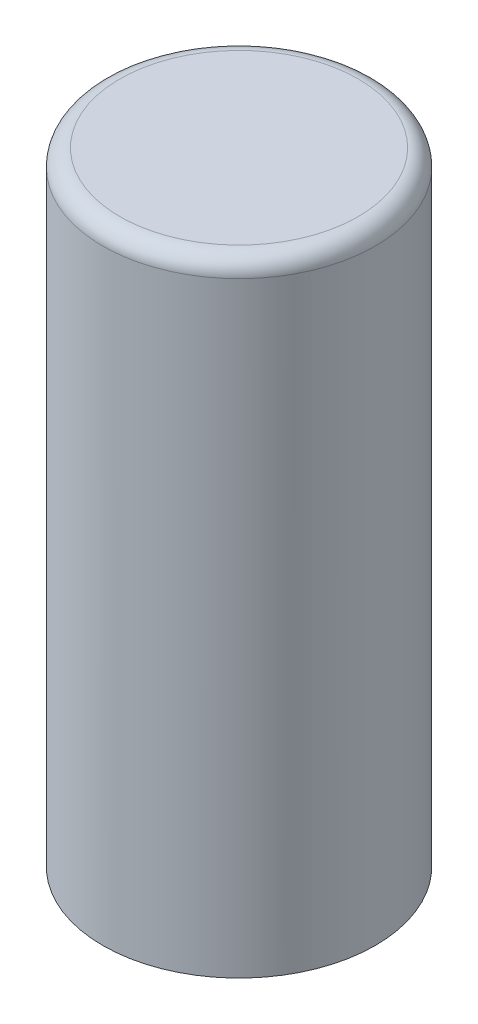
SolidWorks part; units mm, degrees
material "6061-T6 (SS)"
ref_plane "Front Plane" through (0, 0, 0) normal (0, 0, 1) x (1, 0, 0)
ref_plane "Top Plane" through (0, 0, 0) normal (0, 1, 0) x (1, 0, 0)
ref_plane "Right Plane" through (0, 0, 0) normal (1, 0, 0) x (0, 0, -1)
sketch "Sketch1" plane through (0, 0, 0) normal (0, 1, 0) x (1, 0, 0)
  circle A0 centre (0, 0) radius 12.7
  dimension "D1" = 25.4
extrude "Boss-Extrude1" add sketch "Sketch1" along normal offset from surface (58.039 mm away) 132.207
fillet "Fillet1" radius 1.5875 1 edges at (0, 58.039, -12.7)
shell "Shell1" thickness 0.7874
